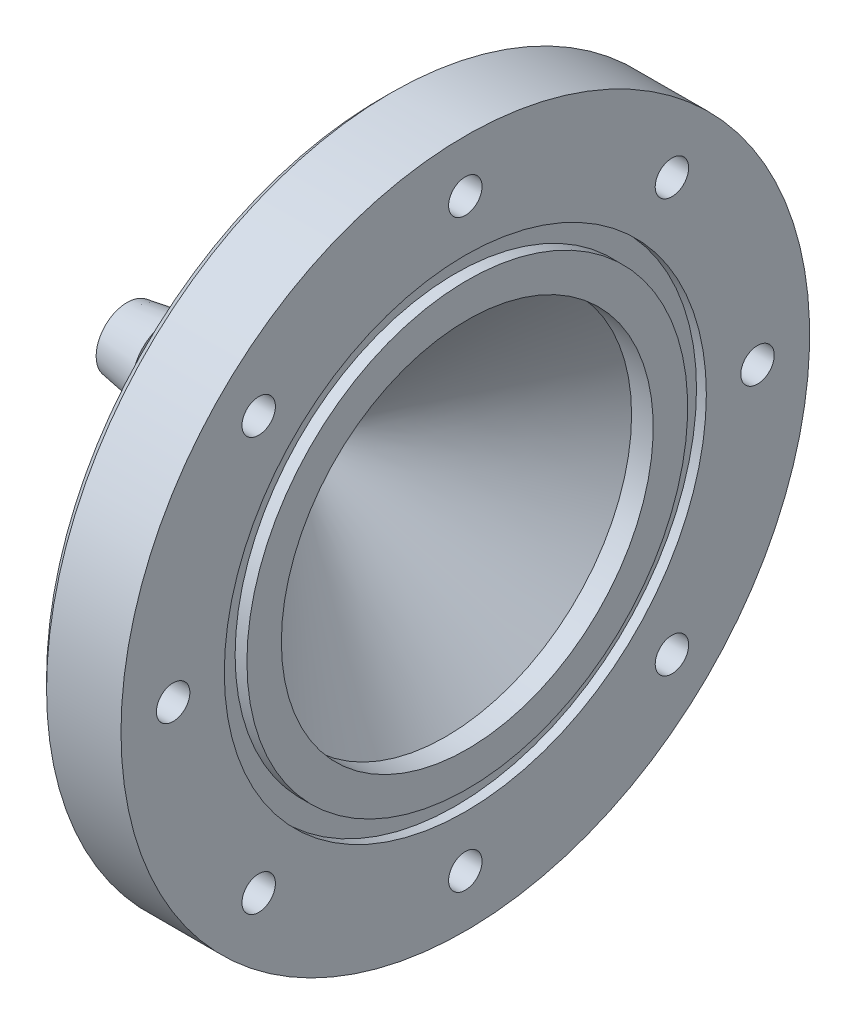
SolidWorks part; units mm, degrees
ref_plane "Front Plane" through (0, 0, 0) normal (0, 0, 1) x (1, 0, 0)
ref_plane "Top Plane" through (0, 0, 0) normal (0, 1, 0) x (1, 0, 0)
ref_plane "Right Plane" through (0, 0, 0) normal (1, 0, 0) x (0, 0, -1)
sketch "Sketch1" plane through (0, 0, 0) normal (0, 0, 1) x (1, 0, 0)
  line L0 (-801.9206, 0) -> (36107.5283, 0) construction
  line L3 (-13.5729, 3.85) -> (-13.5729, 3.15)
  line L8 (-17.9062, 1.9) -> (0, 1.9)
  line L9 (-17.9062, 1.9) -> (-17.9062, 3.15)
  line L10 (16.4699, 24.5) -> (16.4699, 35)
  line L12 (16.4699, 35) -> (7.9039, 35)
  line L16 (16.4699, 24.5) -> (15.4699, 24.5)
  line L17 (15.4699, 24.5) -> (15.4699, 18.9)
  line L18 (7.9039, 35) -> (7.9039, 18.9)
  line L20 (0, 1.9) -> (14.4699, 18.9)
  line L21 (-17.9062, 3.15) -> (-13.5729, 3.85)
  line L22 (14.4699, 18.9) -> (15.4699, 18.9)
  line L23 (-13.5729, 3.15) -> (-9.2395, 3.85)
  line L25 (-9.2395, 3.15) -> (-4.9062, 3.85)
  line L26 (-9.2395, 3.85) -> (-9.2395, 3.15)
  line L27 (-4.9062, 3.85) -> (7.9039, 18.9)
  line L33 (15.4699, 22.4) -> (16.6699, 22.4)
  line L34 (16.6699, 22.4) -> (16.6699, 18.9)
  line L35 (16.6699, 18.9) -> (15.4699, 18.9)
  dimension "D3" = 1
  dimension "D2" = 7.7
  dimension "D6" = 3.8
  dimension "D7" = 6.3
  dimension "D5" = 35
  dimension "D8" = 24.5
  dimension "D4" = 5
  dimension "D9" = 1
  dimension "D11" = 13
  dimension "D12" = 8.566
  dimension "D16" = 3.5
  dimension "D10" = 2.1
  dimension "D13" = 0.2
revolve "Revolve17" add sketch "Sketch1" angle 360 about L0
sketch "Sketch4" plane through (7.9039, 0, 0) normal (-1, 0, 0) x (0, 0, 1)
  line L0 (0, 18.9) -> (0, 35) construction
  circle A0 centre (0, 0) radius 29.7 construction
  circle A1 centre (0, 0) radius 18.9 construction
  circle A2 centre (0, 0) radius 35 construction
  point P3 (0, 29.7)
  point P7 (29.7, 0)
  point P12 (-29.7, 0)
  point P13 (0, -29.7)
  point P22 (-21.0011, 20.8472)
  point P25 (21.0011, 20.8472)
  point P28 (21.0011, -21.1549)
  point P31 (-21.0011, -21.1549)
  dimension "D1" = 5.3
  dimension "D2" = 5.3
hole_wizard "CBORE for M3 Hex Socket Head Cap Screw2" positions "Sketch4" profile "Sketch5" counterbore size "M3" standard "ISO"
sketch "Sketch5" plane through (7.9039, -21.1549, -21.0011) normal (0, 1, 0) x (0, 0, 1)
  line L0 (0, 0) -> (0, 9.5875)
  line L1 (0, 9.5875) -> (1.7, 8.566)
  line L2 (1.7, 8.566) -> (1.7, 3.4)
  line L3 (1.7, 3.4) -> (3.25, 3.4)
  line L4 (3.25, 3.4) -> (3.25, 0)
  line L5 (3.25, 0) -> (0, 0)
  line L10 (0, 9.5875) -> (-1.7, 8.566) construction
  line L11 (0, -6.35) -> (0, 107.95) construction
  dimension "Hole Dia." = 3.4
  dimension "Hole Depth" = 8.566
  dimension "C'Bore Dia." = 6.5
  dimension "C'Bore Depth" = 3.4
  dimension "Drill Angle" = 118
chamfer "Chamfer1" distance 1 angle 45 1 edges at (7.9039, 0, 35)
sketch "Sketch6" plane through (16.4699, 0, 0) normal (1, 0, 0) x (0, 0, -1)
  line L0 (0, 35) -> (0, 24.5)
  circle A0 centre (0, 0) radius 35
  circle A1 centre (0, 0) radius 35 construction
  circle A2 centre (0, 0) radius 24.5 construction
equation "\"D9@Sketch1\"=\"D3@Sketch1\""
